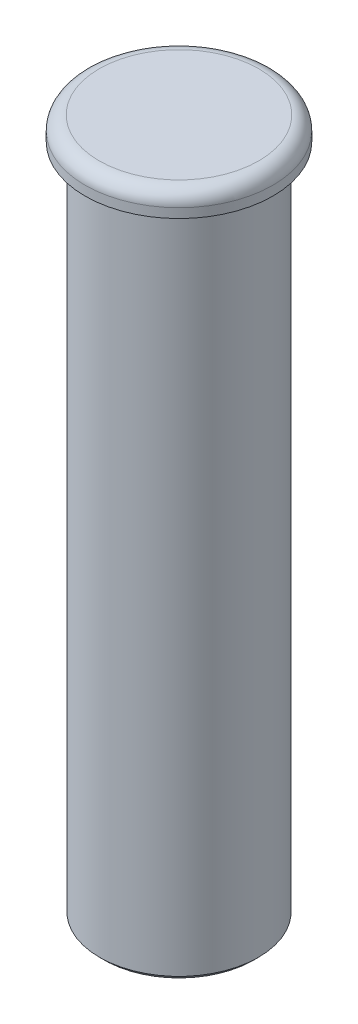
SolidWorks part; units mm, degrees
ref_plane "Piano frontale" through (0, 0, 0) normal (0, 0, 1) x (1, 0, 0)
ref_plane "Piano superiore" through (0, 0, 0) normal (0, 1, 0) x (1, 0, 0)
ref_plane "Piano destro" through (0, 0, 0) normal (1, 0, 0) x (0, 0, -1)
sketch "Schizzo1" plane through (0, 0, 0) normal (0, 0, 1) x (1, 0, 0)
  line L0 (-10, 37) -> (0, 37)
  line L1 (0, 37) -> (0, -37) construction
  line L2 (0, -37) -> (-8.45, -37)
  line L3 (-8.45, -37) -> (-8.45, 34.5)
  line L4 (-8.45, 34.5) -> (-10, 34.5)
  line L5 (-10, 34.5) -> (-10, 37)
  line L6 (0, 37) -> (0, -37)
  point P5 (0, 0)
  dimension "D1" = 2.5
  dimension "D2" = 74
  dimension "D3" = 16.9
  dimension "D4" = 20
revolve "Rivoluzione1" add sketch "Schizzo1" angle 360 about L1
fillet "Raccordo1" radius 1.5 1 edges at (0, 37, 10)
fillet "Raccordo2" radius 0.5 1 edges at (0, 34.5, 8.45)
chamfer "Smusso1" distance 0.5 angle 45 1 edges at (0, -37, 8.45)
